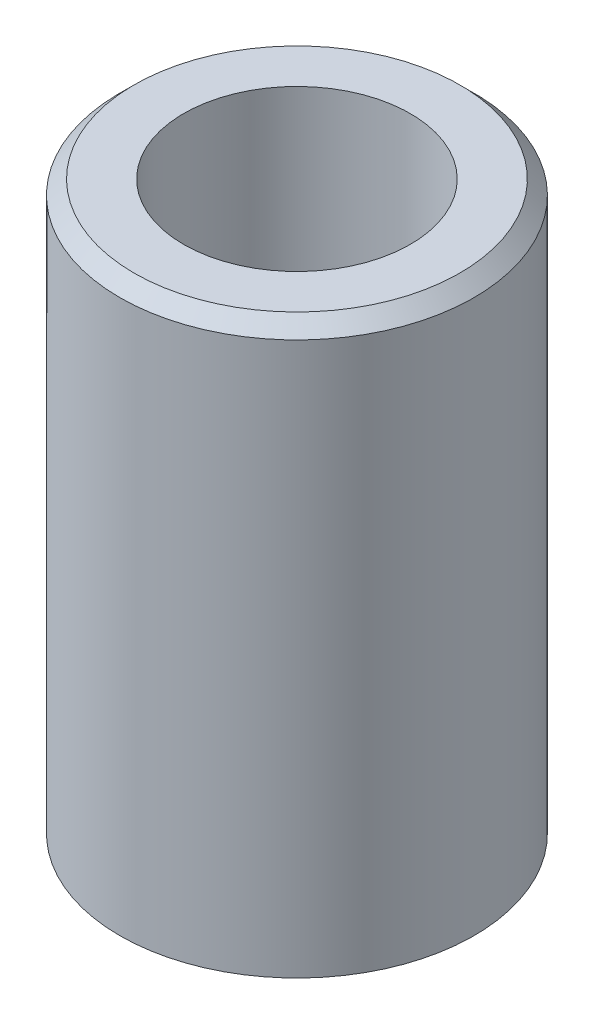
SolidWorks part; units mm, degrees
ref_plane "Front Plane" through (0, 0, 0) normal (0, 0, 1) x (1, 0, 0)
ref_plane "Top Plane" through (0, 0, 0) normal (0, 1, 0) x (1, 0, 0)
ref_plane "Right Plane" through (0, 0, 0) normal (1, 0, 0) x (0, 0, -1)
sketch "Sketch1" plane through (0, 0, 0) normal (0, 1, 0) x (1, 0, 0)
  circle A0 centre (0, 0) radius 1.6
  circle A1 centre (0, 0) radius 2.5
  dimension "D1" = 3.2
  dimension "D2" = 5
extrude "Boss-Extrude1" add sketch "Sketch1" along normal blind 8
chamfer "Chamfer1" distance 0.2 angle 45 1 edges at (0, 8, 2.5)
